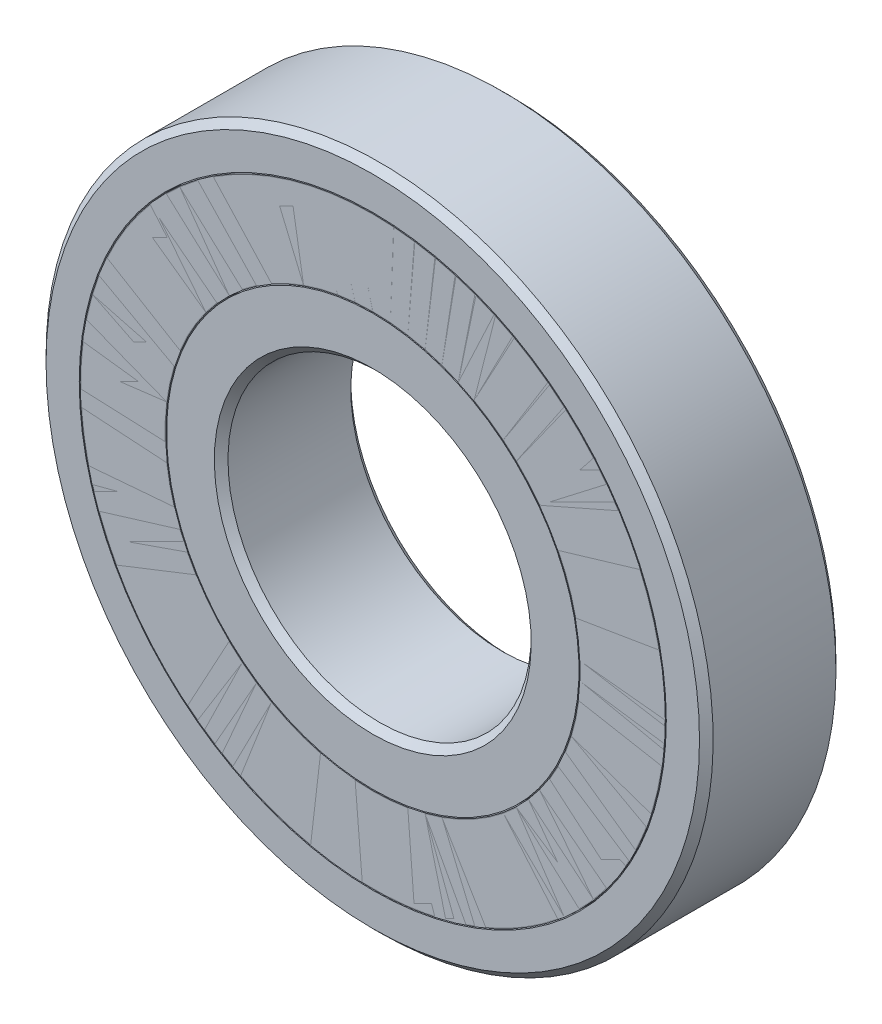
SolidWorks part; units mm, degrees
ref_plane "Front Plane" through (0, 0, 0) normal (0, 0, 1) x (1, 0, 0)
ref_plane "Top Plane" through (0, 0, 0) normal (0, 1, 0) x (1, 0, 0)
ref_plane "Right Plane" through (0, 0, 0) normal (1, 0, 0) x (0, 0, -1)
sketch "Sketch1" plane through (0, 0, 0) normal (0, 0, 1) x (1, 0, 0)
  line L0 (-17.4625, 0) -> (17.4625, 0) construction
  line L1 (-7.9375, 0) -> (7.9375, 0) construction
  circle A0 centre (0, 0) radius 7.9375 construction
  circle A1 centre (0, 0) radius 17.4625 construction
  point P3 (0, 0)
  point P6 (0, 0)
  point P7 (0, -7.9375)
  point P11 (0, -17.4625)
  point P12 (0, 7.9375)
  point P13 (0, 17.4625)
  dimension "OD" = 34.925
  dimension "ID" = 15.875
sketch "Sketch2" plane through (0, 0, 0) normal (1, 0, 0) x (0, 0, -1)
  line L0 (-3.5719, 17.4625) -> (3.5719, 17.4625) construction
  line L1 (0, 17.4625) -> (0, -17.4625) construction
  line L2 (3.2147, 17.4625) -> (-3.2147, 17.4625)
  line L3 (-3.2147, 17.4625) -> (-3.5719, 17.1053)
  line L4 (-3.5719, 17.1053) -> (-3.5719, 15.367)
  line L5 (-3.5719, 15.367) -> (-1.5875, 15.367)
  line L6 (3.5719, 15.367) -> (1.5875, 15.367)
  line L7 (3.5719, 17.1053) -> (3.5719, 15.367)
  line L8 (3.2147, 17.4625) -> (3.5719, 17.1053)
  line L9 (0, 17.4625) -> (0, 12.7) construction
  line L10 (0, 12.7) -> (0, 7.9375) construction
  line L11 (0, 17.4625) -> (0, -17.4625) construction
  line L12 (-3.5719, 0) -> (3.5719, 0) construction
  line L13 (3.5719, 7.9375) -> (-3.5719, 7.9375) construction
  line L15 (-3.5719, -7.9375) -> (3.5719, -7.9375) construction
  line L16 (-3.5719, 7.9375) -> (-3.5719, -7.9375) construction
  line L17 (3.5719, 17.4625) -> (3.5719, -17.4625) construction
  arc A0 (-1.5875, 15.367) -> (1.5875, 15.367) centre (0, 12.7) cw
  point P14 (0, 7.9375)
  point P17 (0, 0)
  point P21 (0, 17.4625)
  point P29 (0, 7.9375)
  point P30 (0, -7.9375)
  point P34 (-3.5719, 7.9375)
  point P37 (3.5719, 17.4625)
  dimension "Width" = 7.1437
  dimension "D1" = 45
  dimension "Approx. Chamfer" = 0.3572
  dimension "Approx. Ball Seat" = 3.175
  dimension "For Shaft Diameter" = 15.875
  dimension "For Housing ID" = 34.925
  dimension "D2" = 2.0955
sketch "Sketch3" plane through (0, 0, 0) normal (1, 0, 0) x (0, 0, -1)
  line L0 (3.2147, 17.4625) -> (3.5719, 17.1053) construction
  line L1 (3.5719, 17.1053) -> (3.5719, 15.367) construction
  line L2 (3.5719, 15.367) -> (1.5875, 15.367) construction
  line L3 (-3.5719, 15.367) -> (-1.5875, 15.367) construction
  line L4 (-3.5719, 17.1053) -> (-3.5719, 15.367) construction
  line L5 (-3.2147, 17.4625) -> (-3.5719, 17.1053) construction
  line L6 (3.2147, 17.4625) -> (-3.2147, 17.4625) construction
  line L7 (3.2147, 17.4625) -> (3.5719, 17.1053)
  line L8 (3.5719, 17.1053) -> (3.5719, 15.367)
  line L9 (3.5719, 15.367) -> (1.5875, 15.367)
  line L10 (-3.5719, 15.367) -> (-1.5875, 15.367)
  line L11 (-3.5719, 17.1053) -> (-3.5719, 15.367)
  line L12 (-3.2147, 17.4625) -> (-3.5719, 17.1053)
  line L13 (3.2147, 17.4625) -> (-3.2147, 17.4625)
  arc A0 (1.5875, 15.367) -> (-1.5875, 15.367) centre (0, 12.7) ccw construction
  arc A1 (1.5875, 15.367) -> (-1.5875, 15.367) centre (0, 12.7) ccw
revolve "Revolve1" add sketch "Sketch3" angle 360 about L12
sketch "Sketch4" plane through (0, 0, 0) normal (1, 0, 0) x (0, 0, -1)
  line L1 (-3.5719, 17.1053) -> (-3.5719, -17.1053) construction
  line L2 (-3.2147, 7.9375) -> (-3.5719, 8.2947)
  line L3 (-3.5719, 8.2947) -> (-3.5719, 10.795)
  line L4 (-3.5719, 10.795) -> (-1.5875, 10.795)
  line L5 (3.5719, 8.2947) -> (3.5719, 10.795)
  line L6 (-3.2147, 7.9375) -> (3.2147, 7.9375)
  line L7 (3.5719, 17.4625) -> (3.5719, -17.4625) construction
  line L8 (3.2147, 7.9375) -> (3.5719, 8.2947)
  line L9 (3.5719, 10.795) -> (1.5875, 10.795)
  line L13 (3.2147, 17.4625) -> (3.5719, 17.1053) construction
  line L16 (3.2147, 17.4625) -> (3.2147, -17.4625) construction
  arc A1 (-1.5875, 10.795) -> (1.5875, 10.795) centre (0, 13.462) ccw
  arc A2 (1.5875, 15.367) -> (-1.5875, 15.367) centre (0, 12.7) ccw construction
  point P1 (0, 7.9375)
  dimension "D1" = 45
  dimension "D2" = 2.8575
revolve "Revolve2" add sketch "Sketch4" angle 360 about L12
sketch "Sketch7" plane through (0, 12.7, -3.5719) normal (0, 0, -1) x (-1, 0, 0)
  circle A2 centre (0, -12.7) radius 10.8458
  circle A4 centre (0, -12.7) radius 10.8458
  circle A5 centre (0, -12.7) radius 15.3162
  circle A6 centre (0, -12.7) radius 15.3162
  dimension "D1" = 0.0508
  dimension "D2" = 0.0508
extrude "Boss-Extrude2" add sketch "Sketch7" against normal up to surface (7.1437 mm away) separate body up to face at (0, -15.367, 3.5719)
fillet "Fillet1" radius 0.0318 2 edges at (0, 10.8458, 3.5719) (0, 15.3162, 3.5719)
mirror "Mirror1" about plane through (0, 0, 0) normal (0, 0, 1) of bodies 145
equation "\"Approx. Chamfer@Sketch2\" = \"Width@Sketch2\" * .05"
equation "\"Approx. Ball Seat@Sketch2\" = \"Width@Sketch2\" / 2.25"
equation "\"D2@Sketch2\"=(\"For Housing ID@Sketch2\"-\"For Shaft Diameter@Sketch2\")*.11"
equation "\"D2@Sketch4\"=(\"For Housing ID@Sketch2\"-\"For Shaft Diameter@Sketch2\")*.15"
